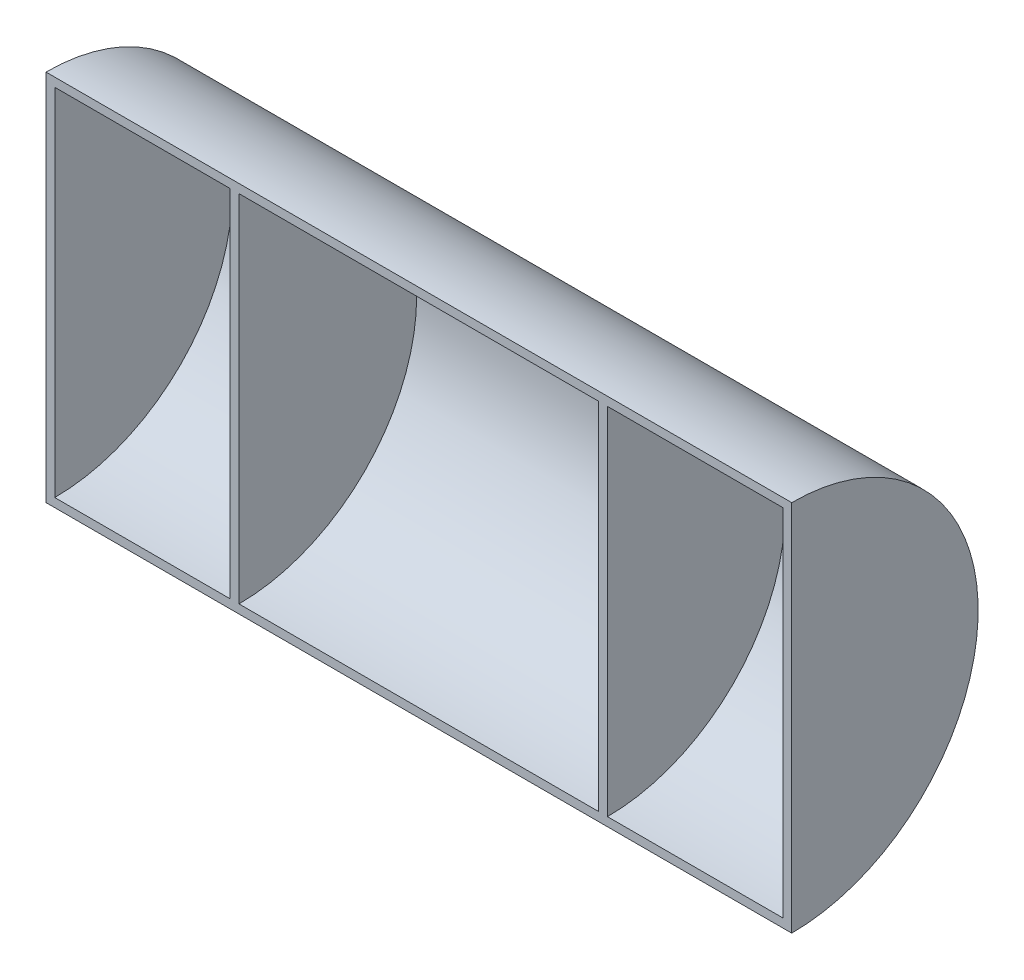
SolidWorks part; units mm, degrees
ref_plane "Front Plane" through (0, 0, 0) normal (0, 0, 1) x (1, 0, 0)
ref_plane "Top Plane" through (0, 0, 0) normal (0, 1, 0) x (1, 0, 0)
ref_plane "Right Plane" through (0, 0, 0) normal (1, 0, 0) x (0, 0, -1)
sketch "Profile Sketch" plane through (0, 0, 0) normal (1, 0, 0) x (0, 0, -1)
  line L0 (0, 42.5) -> (0, -42.5)
  arc A0 (0, -42.5) -> (0, 42.5) centre (0, 0) ccw
  dimension "D1" = 85
extrude "Profile Extrude" add sketch "Profile Sketch" against normal blind 170
shell "Profile Shell" thickness 2
sketch "Support Sketch" plane through (0, 0, 0) normal (0, 0, 1) x (1, 0, 0)
  line L0 (-168, 40.5) -> (-2, 40.5) construction
  line L1 (-168, -40.5) -> (-2, -40.5) construction
  line L2 (-128, 40.5) -> (-126, 40.5)
  line L3 (-128, 40.5) -> (-128, -40.5)
  line L4 (-128, -40.5) -> (-126, -40.5)
  line L5 (-126, 40.5) -> (-126, -40.5)
  line L6 (-128, 40.5) -> (-126, -40.5) construction
  line L7 (-128, -40.5) -> (-126, 40.5) construction
  line L8 (-168, -40.5) -> (-168, 40.5) construction
  line L9 (-44, 40.5) -> (-42, 40.5)
  line L10 (-44, 40.5) -> (-44, -40.5)
  line L11 (-44, -40.5) -> (-42, -40.5)
  line L12 (-42, 40.5) -> (-42, -40.5)
  line L13 (-44, 40.5) -> (-42, -40.5) construction
  line L14 (-44, -40.5) -> (-42, 40.5) construction
  line L15 (-2, 40.5) -> (-2, -40.5) construction
  point P1 (-127, 0)
  point P7 (-43, 0)
  dimension "D1" = 2
  dimension "D2" = 2
  dimension "D3" = 40
  dimension "D4" = 40
extrude "Support Extrude" add sketch "Support Sketch" against normal up to surface up to face at (-85, 0, -20.25)
sketch "Angle Sketch" plane through (0, 0, 0) normal (1, 0, 0) x (0, 0, -1)
  line L0 (0, 0) -> (42.5, 0) construction
  arc A0 (0, -42.5) -> (0, 42.5) centre (0, 0) ccw construction
  point P7 (42.5, 0)
